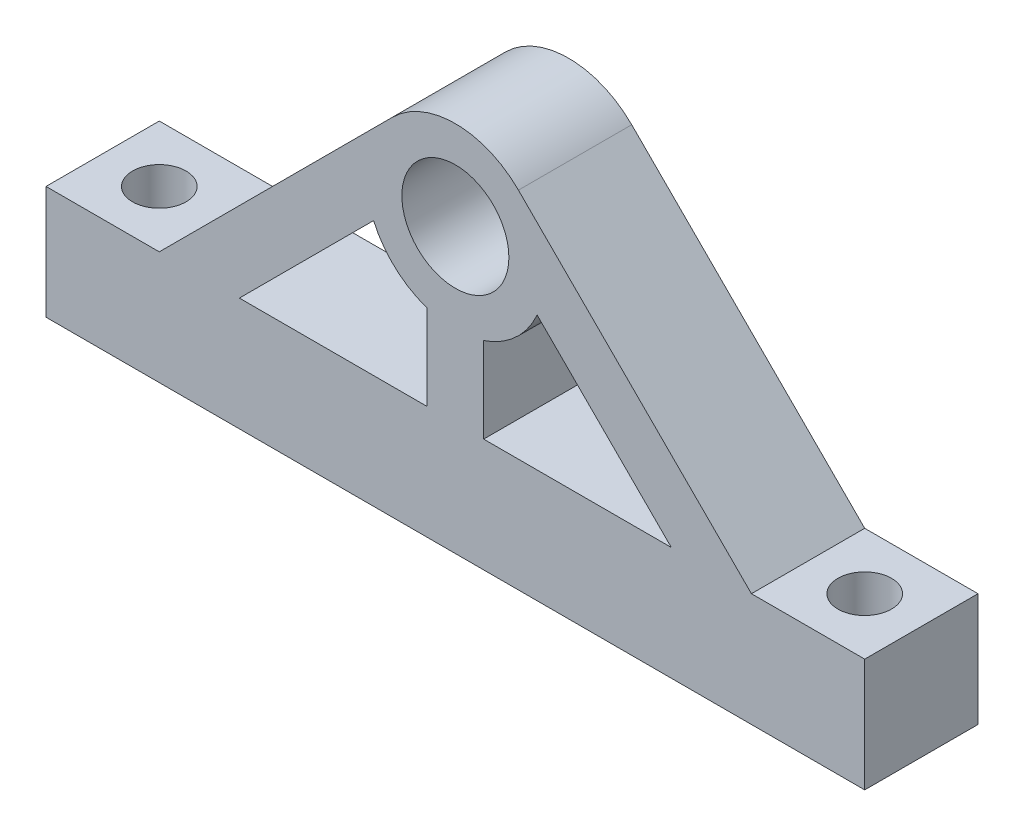
SolidWorks part; units mm, degrees
material "Pine"
ref_plane "Front Plane" through (0, 0, 0) normal (0, 0, 1) x (1, 0, 0)
ref_plane "Top Plane" through (0, 0, 0) normal (0, 1, 0) x (1, 0, 0)
ref_plane "Right Plane" through (0, 0, 0) normal (1, 0, 0) x (0, 0, -1)
sketch "Sketch1" plane through (0, 0, 0) normal (0, 0, 1) x (1, 0, 0)
  line L0 (-3.5355, 3.5355) -> (-16.5961, -9.525)
  line L1 (3.5355, 3.5355) -> (16.5961, -9.525)
  line L2 (-1.5875, -4.7413) -> (-1.5875, -9.525)
  line L3 (-4.5821, -2.0011) -> (-12.1059, -9.525)
  line L4 (1.5875, -4.7413) -> (1.5875, -9.525)
  line L5 (4.5821, -2.0011) -> (12.1059, -9.525)
  line L7 (-22.9461, -15.875) -> (22.9461, -15.875)
  line L8 (-22.9461, -15.875) -> (-22.9461, -9.525)
  line L9 (-22.9461, -9.525) -> (22.9461, -9.525)
  line L10 (22.9461, -15.875) -> (22.9461, -9.525)
  line L11 (-22.9461, -15.875) -> (22.9461, -9.525) construction
  line L12 (-22.9461, -9.525) -> (22.9461, -15.875) construction
  circle A0 centre (0, 0) radius 3
  circle A1 centre (0, 0) radius 5
  point P15 (0, -12.7)
  dimension "D1" = 6
  dimension "D2" = 10
  dimension "D3" = 3.175
  dimension "D4" = 3.175
  dimension "D5" = 1.5875
  dimension "D6" = 6.35
  dimension "D7" = 6.35
  dimension "D8" = 45
  dimension "D9" = 12.7
extrude "Boss-Extrude1" add sketch "Sketch1" along normal blind 6.35 contours A1 A0 | A1 L0 L9 L3 | L7 L10 L9 L8 | A1 L2 L9 L4 | A1 L5 L9 L1
sketch "Sketch2" plane through (0, -9.525, 0) normal (0, 1, 0) x (1, 0, 0)
  line L0 (19.7711, -6.35) -> (19.7711, 0) construction
  line L1 (16.5961, -6.35) -> (22.9461, -6.35) construction
  line L2 (16.5961, 0) -> (22.9461, 0) construction
  line L3 (-19.7711, -6.35) -> (-19.7711, 0) construction
  line L4 (-22.9461, -6.35) -> (-16.5961, -6.35) construction
  line L5 (-22.9461, 0) -> (-16.5961, 0) construction
  circle A0 centre (19.7711, -3.175) radius 1.5
  circle A1 centre (-19.7711, -3.175) radius 1.5
  point P16 (0, 0)
  dimension "D1" = 3
  dimension "D2" = 3
extrude "Cut-Extrude1" cut sketch "Sketch2" against normal through all
equation "\"D4@Sketch1\"=\"D3@Sketch1\""
equation "\"D5@Sketch1\"=\"D3@Sketch1\"/2"
equation "\"D2@Sketch2\"=\"D1@Sketch2\""
